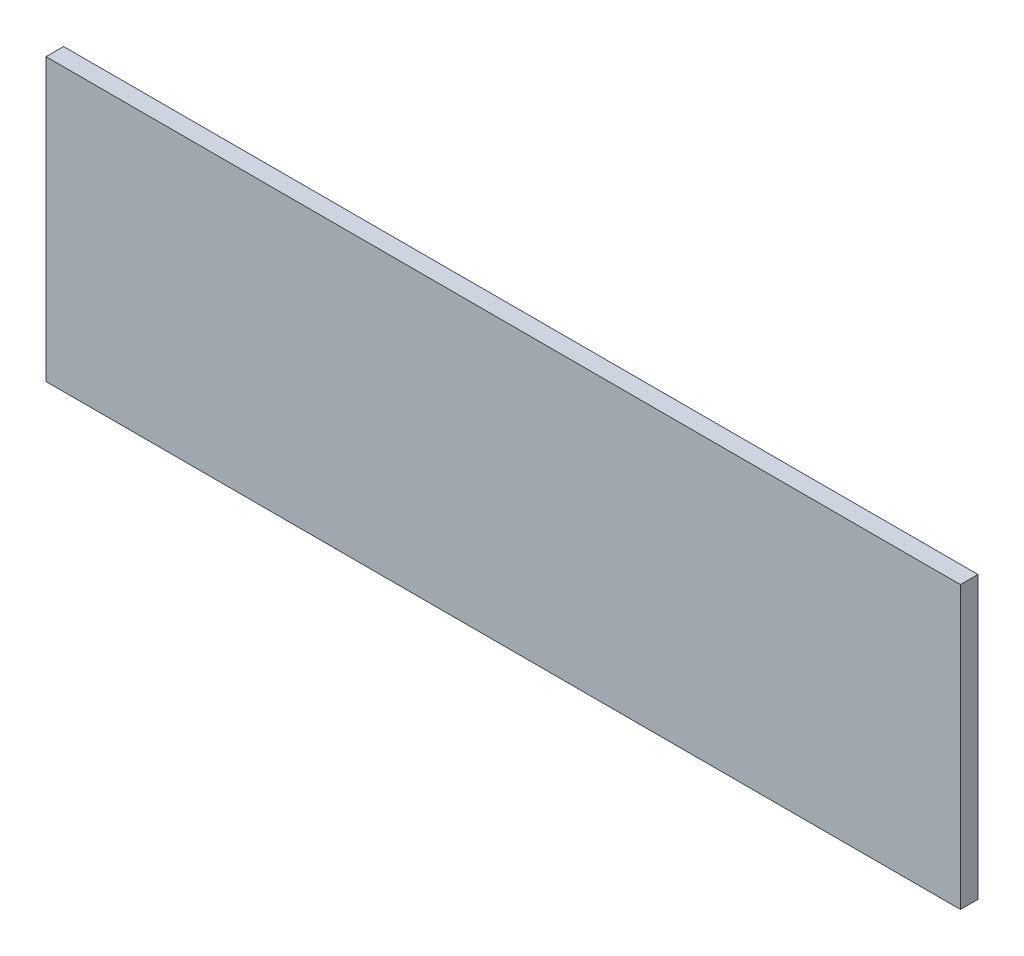
SolidWorks part; units mm, degrees
ref_plane "Front Plane" through (0, 0, 0) normal (0, 0, 1) x (1, 0, 0)
ref_plane "Top Plane" through (0, 0, 0) normal (0, 1, 0) x (1, 0, 0)
ref_plane "Right Plane" through (0, 0, 0) normal (1, 0, 0) x (0, 0, -1)
sketch "Sketch1" plane through (0, 0, 0) normal (0, 0, 1) x (1, 0, 0)
  line L1 (0, 0) -> (82.55, 0)
  line L2 (0, 0) -> (0, 25.4)
  line L3 (0, 25.4) -> (82.55, 25.4)
  line L4 (82.55, 0) -> (82.55, 25.4)
  dimension "D1" = 82.55
  dimension "D2" = 25.4
extrude "Boss-Extrude1" add sketch "Sketch1" along normal blind 1.5875
